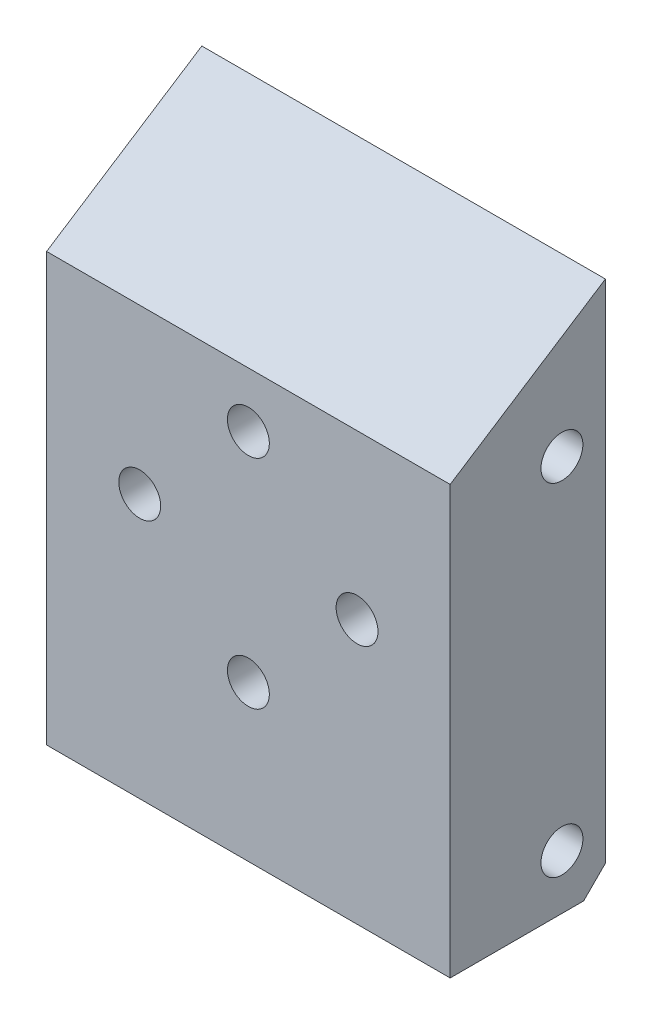
SolidWorks part; units mm, degrees
ref_plane "Plano frontal" through (0, 0, 0) normal (0, 0, 1) x (1, 0, 0)
ref_plane "Plano superior" through (0, 0, 0) normal (0, 1, 0) x (1, 0, 0)
ref_plane "Plano direito" through (0, 0, 0) normal (1, 0, 0) x (0, 0, -1)
sketch "Esboço1" plane through (0, 0, 0) normal (0, 0, 1) x (1, 0, 0)
  line L1 (-13, -17) -> (13, -17)
  line L2 (-13, -17) -> (-13, 17)
  line L3 (-13, 17) -> (13, 17)
  line L4 (13, -17) -> (13, 17)
  line L5 (-13, -17) -> (13, 17) construction
  line L6 (-13, 17) -> (13, -17) construction
  point P0 (0, 0)
extrude "Ressalto-extrusão1" add sketch "Esboço1" along normal blind 10
chamfer "Chanfro2" distance 1.4 angle 45 1 edges at (0, -17, 0)
sketch "Esboço5" plane through (0, 0, 0) normal (1, 0, 0) x (0, 0, -1)
  line L0 (0, 17) -> (-10, 17)
  line L1 (-10, 17) -> (-10, 10.5381)
  line L2 (-10, -17) -> (-10, 17) construction
  line L3 (-10, 10.5381) -> (0, 17)
extrude "Corte-extrusão1" cut sketch "Esboço5" against normal through all both and the other way through all
ref_plane "Plano6" through (13, 0, 0) normal (1, 0, 0) x (0, 0, -1)
sketch "Esboço8" plane through (13, 0, 0) normal (1, 0, 0) x (0, 0, -1)
  line L0 (0, -15.6) -> (0, 17) construction
  circle A0 centre (-2.8, 8.5) radius 1.35
  circle A1 centre (-2.8, -13.5) radius 1.35
  dimension "D1" = 8.5
  dimension "D3" = 2.8
  dimension "D2" = 2.8
  dimension "D4" = 22
extrude "Corte-extrusão2" cut sketch "Esboço8" against normal blind 10
ref_plane "Plano7" through (-13, 0, 0) normal (-1, 0, 0) x (0, 0, 1)
sketch "Esboço9" plane through (-13, 0, 0) normal (-1, 0, 0) x (0, 0, 1)
  line L1 (0, 17) -> (0, -15.6) construction
  circle A0 centre (2.8, 8.5) radius 1.025
  circle A1 centre (2.8, -13.5) radius 1.025
  dimension "D1" = 8.5
  dimension "D3" = 22
  dimension "D2" = 2.8
extrude "Corte-extrusão3" cut sketch "Esboço9" against normal blind 10
ref_plane "Plano8" through (0, 0, 10) normal (0, 0, 1) x (1, 0, 0)
sketch "Esboço11" plane through (0, 0, 10) normal (0, 0, 1) x (1, 0, 0)
  circle A0 centre (7, 0) radius 1.35
  circle A1 centre (0, -7) radius 1.35
  circle A2 centre (-7, 0) radius 1.35
  circle A3 centre (0, 7) radius 1.35
  dimension "D1" = 7
  dimension "D2" = 4
extrude "Corte-extrusão5" cut sketch "Esboço11" against normal blind 4
